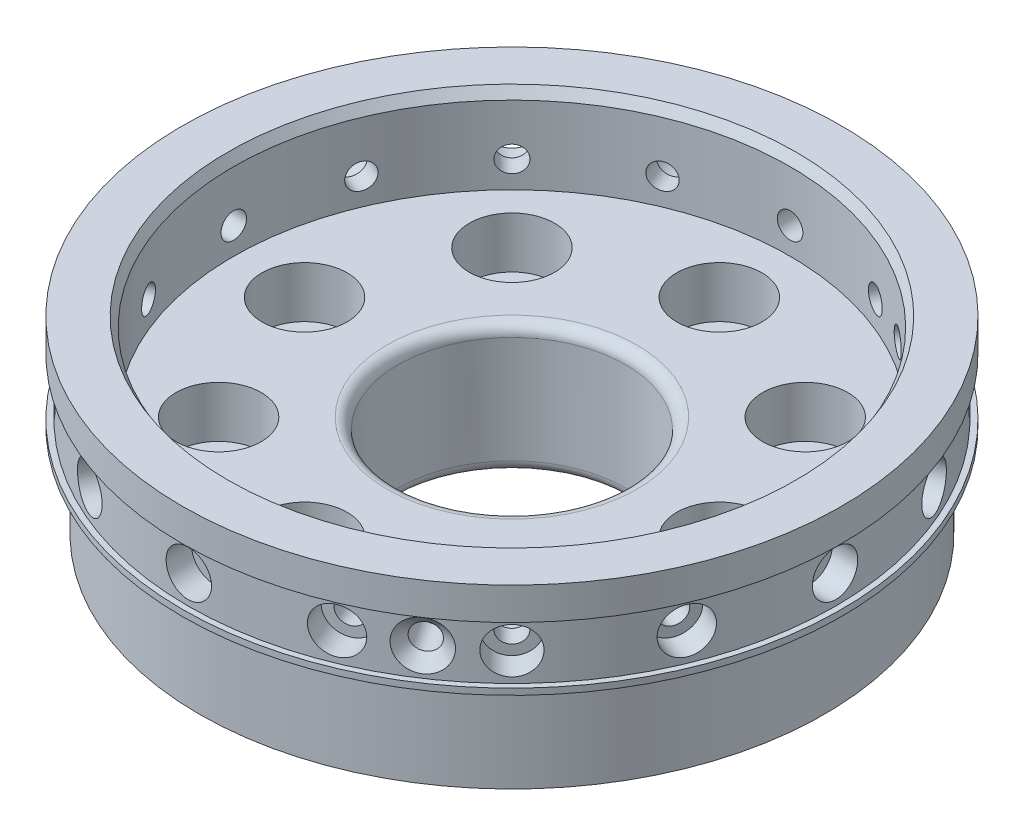
SolidWorks part; units mm, degrees
material "Cast Alloy Steel"
ref_plane "前视" through (0, 0, 0) normal (0, 0, 1) x (1, 0, 0)
ref_plane "上视" through (0, 0, 0) normal (0, 1, 0) x (1, 0, 0)
ref_plane "右视" through (0, 0, 0) normal (1, 0, 0) x (0, 0, -1)
sketch "草图1" plane through (0, 0, 0) normal (0, 0, 1) x (1, 0, 0)
  line L0 (0, 0) -> (0, -150.2913) construction
  line L1 (-55, -16.8) -> (-55, -33.2)
  line L2 (-55, -33.2) -> (-25, -33.2)
  line L3 (-25, -33.2) -> (-25, -38.2)
  line L4 (-25, -38.2) -> (-20, -38.2)
  line L5 (-20, -38.2) -> (-20, -15.4)
  line L6 (-49, 0) -> (-58, 0)
  line L7 (-49, 0) -> (-49, -15.4)
  line L8 (-49, -15.4) -> (-20, -15.4)
  line L9 (-55, -16.8) -> (-58, -16.8)
  line L10 (-58, -16.8) -> (-58, 0)
  dimension "D1" = 40
  dimension "D2" = 50
  dimension "D3" = 110
  dimension "D4" = 5
  dimension "D5" = 38.2
  dimension "D6" = 98
  dimension "D7" = 15.4
  dimension "D8" = 116
  dimension "D9" = 16.8
revolve "旋转1" add sketch "草图1" angle 360 about L0
sketch "草图11" plane through (0, 0, 0) normal (0, 1, 0) x (1, 0, 0)
  circle A0 centre (0, 0) radius 58
  circle A1 centre (0, 0) radius 57
  dimension "D1" = 116
  dimension "D2" = 114
extrude "切除-拉伸1" cut sketch "草图11" against normal blind 10 from offset 5.7 offset against normal yes
ref_plane "基准面1" through (57, 0, 0) normal (1, 0, 0) x (0, 0, -1)
ref_plane "基准面2" through (-57, 0, 0) normal (-1, 0, 0) x (0, 0, 1)
hole_wizard "打孔尺寸(%根据)内六角圆柱头螺钉的类型3" positions "草图7" profile "草图8" counterbore size "M4" standard "GB"
sketch "草图7" plane through (57, 0, 0) normal (1, 0, 0) x (0, 0, -1)
  point P0 (0, -10.7)
  dimension "D1" = 10.7
sketch "草图8" plane through (57, -10.7, 0) normal (0, 1, 0) x (0, 0, -1)
  line L0 (0, 0) -> (0, 11.3519)
  line L1 (0, 11.3519) -> (2.25, 10)
  line L2 (2.25, 10) -> (2.25, 4.6)
  line L3 (2.25, 4.6) -> (4, 4.6)
  line L4 (4, 4.6) -> (4, 0)
  line L5 (4, 0) -> (0, 0)
  line L10 (0, 11.3519) -> (-2.25, 10) construction
  line L11 (0, -6.35) -> (0, 107.95) construction
  dimension "孔直径" = 4.5
  dimension "孔深度" = 10
  dimension "柱形沉头孔直径" = 8
  dimension "柱形沉头孔深度" = 4.6
  dimension "导头角度" = 118
pattern_circular "阵列(圆周)2" count 16 over 360 about axis through (0, 0, 0) along (0, 1, 0) skipping 8 of "打孔尺寸(%根据)内六角圆柱头螺钉的类型3"
hole_wizard "打孔尺寸(%根据十字)槽半沉头木螺钉的类型1" positions "草图12" profile "草图13" countersink size "M4" standard "GB" end condition up to next
sketch "草图12" plane through (-57, 0, 0) normal (-1, 0, 0) x (0, 0, 1)
  point P0 (0, -10.7)
  dimension "D1" = 10.7
sketch "草图13" plane through (-57, -10.7, 0) normal (0, 1, 0) x (0, 0, 1)
  line L0 (0, 0) -> (0, 57)
  line L1 (0, 57) -> (2.25, 57)
  line L2 (2.25, 57) -> (2.25, 2.05)
  line L3 (2.25, 2.05) -> (4.3, 0)
  line L5 (4.3, 0) -> (0, 0)
  line L6 (-2.25, 2.05) -> (-4.3, 0) construction
  line L11 (0, -6.35) -> (0, 107.95) construction
  dimension "通孔孔直径" = 4.5
  dimension "通孔孔深度" = 57
  dimension "近端锥形沉头孔直径" = 8.6
  dimension "近端锥形沉头孔角度" = 90
pattern_circular "阵列(圆周)3" count 2 over 123.75 about axis through (0, 0, 0) along (0, 1, 0) of "打孔尺寸(%根据十字)槽半沉头木螺钉的类型1"
pattern_circular "阵列(圆周)4" count 2 over 123.75 about axis through (0, 0, 0) along (0, 1, 0) of "打孔尺寸(%根据十字)槽半沉头木螺钉的类型1"
hole_wizard "打孔尺寸(%根据)内六角圆柱头螺钉的类型4" positions "草图9" profile "草图10" counterbore size "M8" standard "GB" end condition through all
sketch "草图9" plane through (0, -15.4, 0) normal (0, 1, 0) x (1, 0, 0)
  point P0 (0, 36.5)
  dimension "D1" = 36.5
sketch "草图10" plane through (0, -15.4, -36.5) normal (1, 0, 0) x (0, 0, 1)
  line L0 (0, 0) -> (0, 22.8)
  line L1 (0, 22.8) -> (4.5, 22.8)
  line L3 (4.5, 22.8) -> (4.5, 9)
  line L4 (4.5, 9) -> (7.5, 9)
  line L5 (7.5, 9) -> (7.5, 0)
  line L7 (7.5, 0) -> (0, 0)
  line L11 (0, -6.35) -> (0, 107.95) construction
  dimension "通孔孔直径" = 9
  dimension "通孔孔深度" = 22.8
  dimension "柱形沉头孔直径" = 15
  dimension "柱形沉头孔深度" = 9
pattern_circular "阵列(圆周)5" count 8 over 360 about axis through (0, 0, 0) along (0, 1, 0) of "打孔尺寸(%根据)内六角圆柱头螺钉的类型4"
fillet "圆角1" radius 2 2 edges at (0, -38.2, 20) (0, -15.4, 20)
chamfer "倒角1" distance 1 angle 60 1 edges at (0, -38.2, 25)
chamfer "倒角2" distance 1 angle 60 1 edges at (0, 0, 49)
